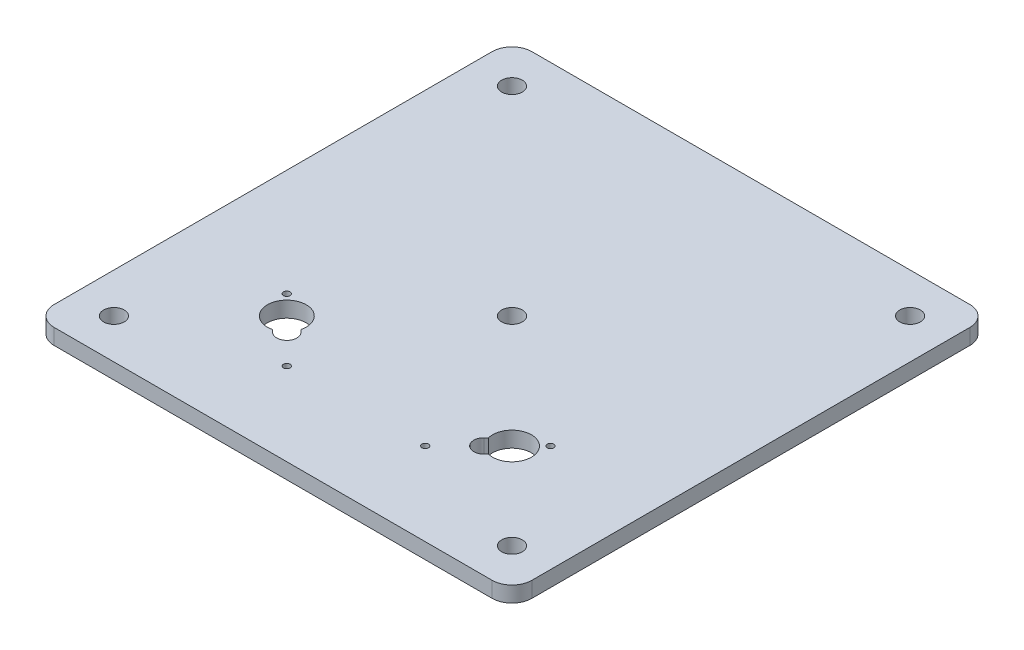
SolidWorks part; units mm, degrees
ref_plane "Front Plane" through (0, 0, 0) normal (0, 0, 1) x (1, 0, 0)
ref_plane "Top Plane" through (0, 0, 0) normal (0, 1, 0) x (1, 0, 0)
ref_plane "Right Plane" through (0, 0, 0) normal (1, 0, 0) x (0, 0, -1)
sketch "Sketch1" plane through (0, 0, 0) normal (0, 1, 0) x (1, 0, 0)
  line L0 (0, 76.2) -> (0, -76.2) construction
  line L1 (-69.85, 76.2) -> (69.85, 76.2)
  line L2 (-76.2, 69.85) -> (-76.2, -69.85)
  line L3 (-69.85, -76.2) -> (69.85, -76.2)
  line L4 (76.2, 69.85) -> (76.2, -69.85)
  line L5 (-76.2, 76.2) -> (76.2, -76.2) construction
  line L6 (-76.2, -76.2) -> (76.2, 76.2) construction
  line L7 (-76.2, 0) -> (76.2, 0) construction
  arc A0 (-76.2, -69.85) -> (-69.85, -76.2) centre (-69.85, -69.85) ccw
  arc A1 (69.85, -76.2) -> (76.2, -69.85) centre (69.85, -69.85) ccw
  arc A2 (69.85, 76.2) -> (76.2, 69.85) centre (69.85, 69.85) cw
  arc A3 (-69.85, 76.2) -> (-76.2, 69.85) centre (-69.85, 69.85) ccw
  circle A5 centre (63.5, 63.5) radius 3.302
  circle A6 centre (63.5, -63.5) radius 3.302
  circle A7 centre (-63.5, -63.5) radius 3.302
  circle A8 centre (-63.5, 63.5) radius 3.302
  circle A9 centre (0, 0) radius 3.302
  circle A10 centre (0, 0) radius 38.1 construction
  circle A11 centre (-35.921, -35.921) radius 12.7 construction
  circle A12 centre (35.921, -35.921) radius 12.7 construction
  point P0 (0, 0)
  dimension "D3" = 6.35
  dimension "D4" = 12.7
  dimension "D5" = 6.604
  dimension "D7" = 6.604
  dimension "D8" = 76.2
  dimension "D9" = 25.4
  dimension "D1" = 152.4
  dimension "D2" = 152.4
  dimension "D6" = 12.7
sketch "Sketch2" plane through (0, 0, 0) normal (0, 1, 0) x (1, 0, 0)
  line L0 (-29.5217, -38.502) -> (-30.4622, -37.5615) construction
  line L1 (-33.3401, -42.3203) -> (-34.2806, -41.3799) construction
  line L2 (-39.9515, -31.8905) -> (-29.5217, -42.3203) construction
  line L3 (-76.2, -76.2) -> (76.2, 76.2) construction
  line L4 (0, -76.2) -> (0, 76.2) construction
  line L5 (39.9515, -31.8905) -> (29.5217, -42.3203) construction
  line L6 (33.3401, -42.3203) -> (34.2806, -41.3799) construction
  line L7 (29.5217, -38.502) -> (30.4622, -37.5615) construction
  line L8 (-39.9162, -31.9259) -> (35315.4229, -35387.2649) construction
  line L9 (-33.6936, -42.6739) -> (-34.4288, -41.9388)
  line L10 (-29.1682, -38.1484) -> (-29.9033, -37.4133)
  line L11 (33.6936, -42.6739) -> (34.4288, -41.9388)
  line L12 (29.1682, -38.1484) -> (29.9033, -37.4133)
  arc A0 (33.3401, -42.3203) -> (29.5217, -38.502) centre (31.4309, -40.4112) cw construction
  arc A2 (-30.4622, -37.5615) -> (-34.2806, -41.3799) centre (-35.921, -35.921) ccw construction
  arc A3 (-33.3401, -42.3203) -> (-29.5217, -38.502) centre (-31.4309, -40.4112) ccw construction
  arc A4 (30.4622, -37.5615) -> (34.2806, -41.3799) centre (35.921, -35.921) cw construction
  circle A5 centre (-42.0552, -29.7869) radius 1.05
  circle A6 centre (-22.0794, -49.7626) radius 1.05
  circle A7 centre (22.0794, -49.7626) radius 1.05
  circle A8 centre (42.0552, -29.7869) radius 1.05
  arc A9 (-29.9033, -37.4133) -> (-34.4288, -41.9388) centre (-35.921, -35.921) ccw
  arc A10 (-33.6936, -42.6739) -> (-29.1682, -38.1484) centre (-31.4309, -40.4112) ccw
  arc A11 (33.6936, -42.6739) -> (29.1682, -38.1484) centre (31.4309, -40.4112) cw
  arc A12 (29.9033, -37.4133) -> (34.4288, -41.9388) centre (35.921, -35.921) cw
  point P8 (-29.5217, -42.3203)
  point P10 (-39.9515, -31.8905)
  dimension "D1" = 90
  dimension "D2" = 11.4
  dimension "D4" = 2.7
  dimension "D8" = 2.1
  dimension "D9" = 28.25
  dimension "D3" = 14.75
  dimension "D5" = 2.7
  dimension "D6" = 2.7
  dimension "D7" = 8.675
  dimension "D10" = 0.5
extrude "Boss-Extrude1" add sketch "Sketch1" along normal blind 5
extrude "Cut-Extrude2" cut sketch "Sketch2" along normal through all
